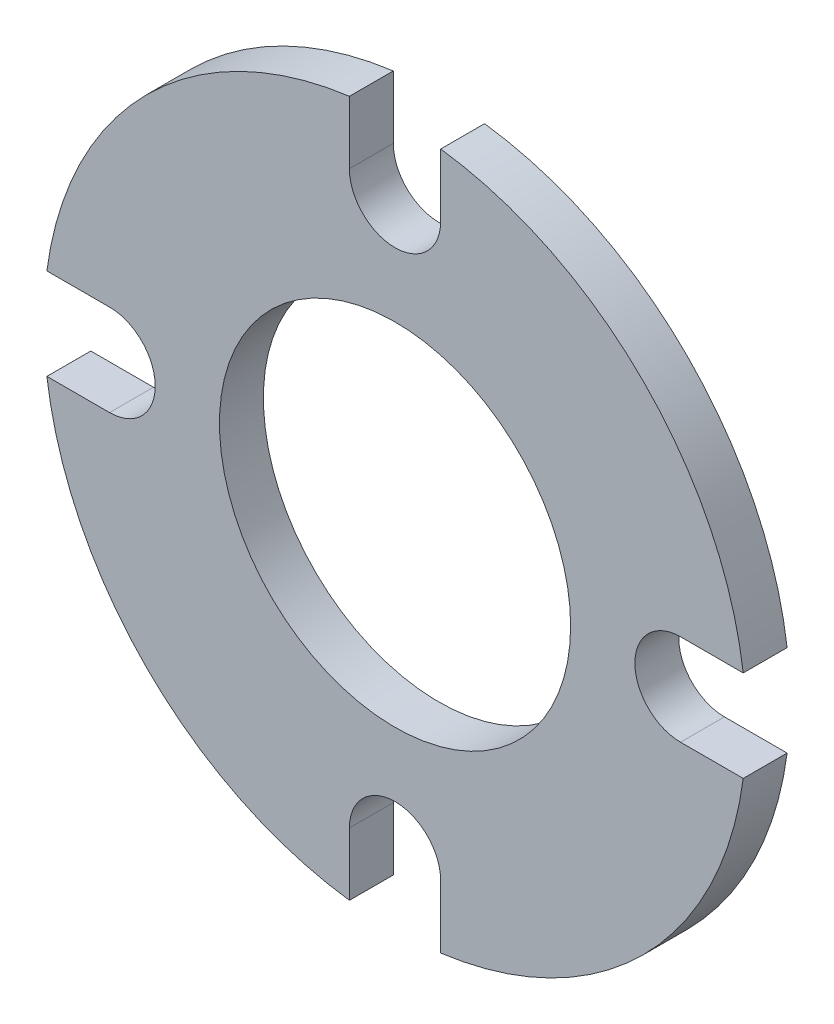
SolidWorks part; units mm, degrees
ref_plane "Front Plane" through (0, 0, 0) normal (0, 0, 1) x (1, 0, 0)
ref_plane "Top Plane" through (0, 0, 0) normal (0, 1, 0) x (1, 0, 0)
ref_plane "Right Plane" through (0, 0, 0) normal (1, 0, 0) x (0, 0, -1)
sketch "Sketch2" plane through (0, 0, 0) normal (0, 0, 1) x (1, 0, 0)
  line L0 (-1, 0) -> (1, 0) construction
  line L1 (0, 1) -> (0, -1) construction
  line L2 (-0.13, -0.813) -> (-0.13, -0.9915)
  line L3 (0.13, -0.813) -> (0.13, -0.9915)
  line L4 (0.13, 0.813) -> (0.13, 0.9915)
  line L5 (-0.13, 0.813) -> (-0.13, 0.9915)
  line L6 (-0.813, 0.13) -> (-0.9915, 0.13)
  line L7 (-0.813, -0.13) -> (-0.9915, -0.13)
  line L8 (0.813, -0.13) -> (0.9915, -0.13)
  line L9 (0.813, 0.13) -> (0.9915, 0.13)
  circle A0 centre (0, 0) radius 0.5
  circle A1 centre (0, 0) radius 1
  arc A2 (0.13, -0.813) -> (-0.13, -0.813) centre (0, -0.813) ccw
  arc A3 (0.13, 0.813) -> (-0.13, 0.813) centre (0, 0.813) cw
  arc A4 (-0.813, -0.13) -> (-0.813, 0.13) centre (-0.813, 0) ccw
  arc A5 (0.813, -0.13) -> (0.813, 0.13) centre (0.813, 0) cw
  dimension "D1" = 2
  dimension "D2" = 1
  dimension "D3" = 0.26
  dimension "D5" = 0.26
  dimension "D4" = 0.813
  dimension "D6" = 0.813
extrude "Boss-Extrude1" add sketch "Sketch2" along normal mid plane 0.125 contours L8 A5 L9 A1 L4 A3 L5 L6 A4 L7 L2 A2 L3 A0
